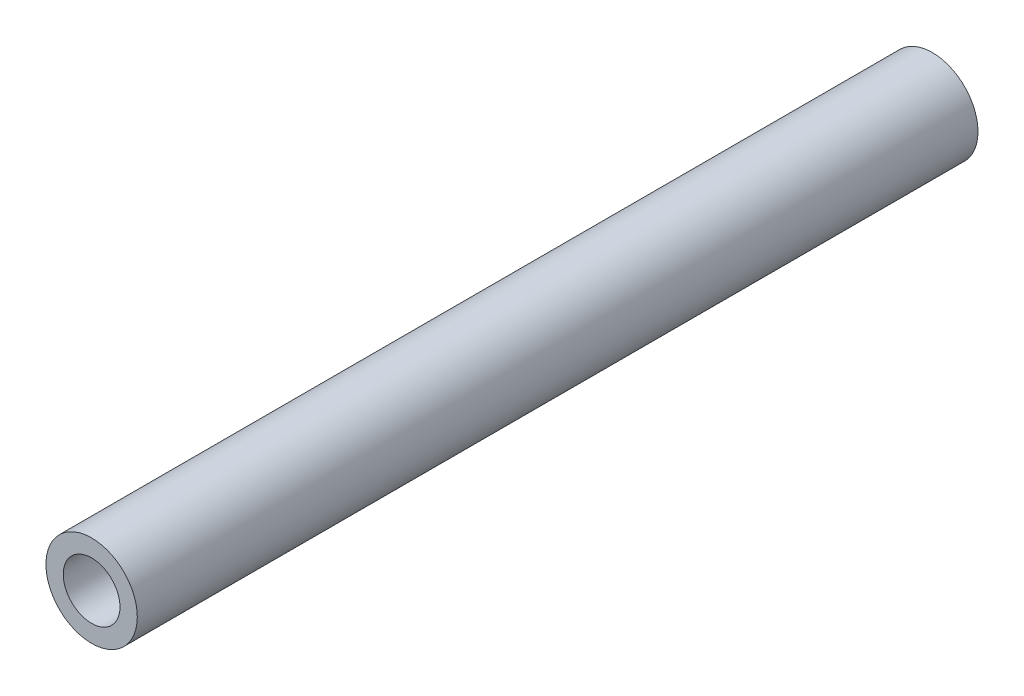
SolidWorks part; units mm, degrees
material "6061-T6 (SS)"
ref_plane "Front Plane" through (0, 0, 0) normal (0, 0, 1) x (1, 0, 0)
ref_plane "Top Plane" through (0, 0, 0) normal (0, 1, 0) x (1, 0, 0)
ref_plane "Right Plane" through (0, 0, 0) normal (1, 0, 0) x (0, 0, -1)
sketch "Sketch1" plane through (0, 0, 0) normal (0, 0, 1) x (1, 0, 0)
  circle A0 centre (0, 0) radius 3.9688
  circle A1 centre (0, 0) radius 2.4638
  dimension "D1" = 4.9276
  dimension "D2" = 7.9375
extrude "Boss-Extrude1" add sketch "Sketch1" along normal blind 73.025
